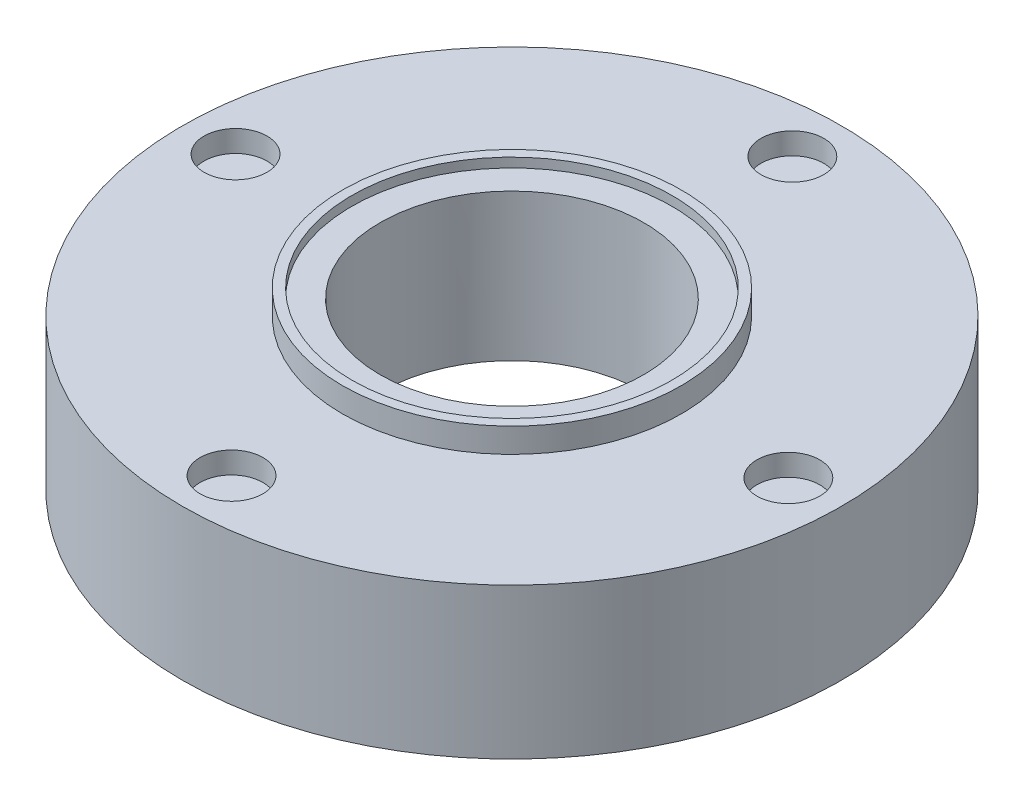
SolidWorks part; units mm, degrees
material "ABS"
ref_plane "Front Plane" through (0, 0, 0) normal (0, 0, 1) x (1, 0, 0)
ref_plane "Top Plane" through (0, 0, 0) normal (0, 1, 0) x (1, 0, 0)
ref_plane "Right Plane" through (0, 0, 0) normal (1, 0, 0) x (0, 0, -1)
sketch "Sketch1" plane through (0, 0, 0) normal (0, 1, 0) x (1, 0, 0)
  circle A0 centre (0, 0) radius 17.5
  dimension "D1" = 35
extrude "Boss-Extrude1" add sketch "Sketch1" along normal blind 8
sketch "Sketch5" plane through (0, 0, 0) normal (0, -1, 0) x (1, 0, 0)
  circle A2 centre (0, 0) radius 16.5
  circle A3 centre (0, 0) radius 16.5
  dimension "D1" = 1
extrude "Cut-Extrude2" cut sketch "Sketch5" against normal blind 1
sketch "Sketch11" plane through (0, 8, 0) normal (0, 1, 0) x (1, 0, 0)
  line L0 (0, 17.5) -> (0, 16.45) construction
  circle A0 centre (0, 0) radius 17.5 construction
  circle A1 centre (0.1067, 14.7834) radius 1.67
  dimension "D2" = 3.34
  dimension "D1" = 1.05
extrude "Cut-Extrude5" cut sketch "Sketch11" against normal blind 1.15
pattern_circular "CirPattern1" count 4 over 360 about axis through (0, 0, 0) along (0, 1, 0) of "Cut-Extrude5"
sketch "Sketch13" plane through (0, 8, 0) normal (0, 1, 0) x (1, 0, 0)
  circle A0 centre (0, 0) radius 9
  circle A1 centre (0, 0) radius 8.5
  dimension "D1" = 18
  dimension "D2" = 17
extrude "Boss-Extrude3" add sketch "Sketch13" along normal blind 1.3
sketch "Sketch12" plane through (0, 8, 0) normal (0, 1, 0) x (1, 0, 0)
  circle A0 centre (0, 0) radius 8.6
extrude "Boss-Extrude2" add sketch "Sketch12" along normal blind 0.8
sketch "Sketch14" plane through (0, 8.8, 0) normal (0, 1, 0) x (1, 0, 0)
  circle A0 centre (0, 0) radius 7
  dimension "D1" = 14
extrude "Cut-Extrude6" cut sketch "Sketch14" against normal through all
